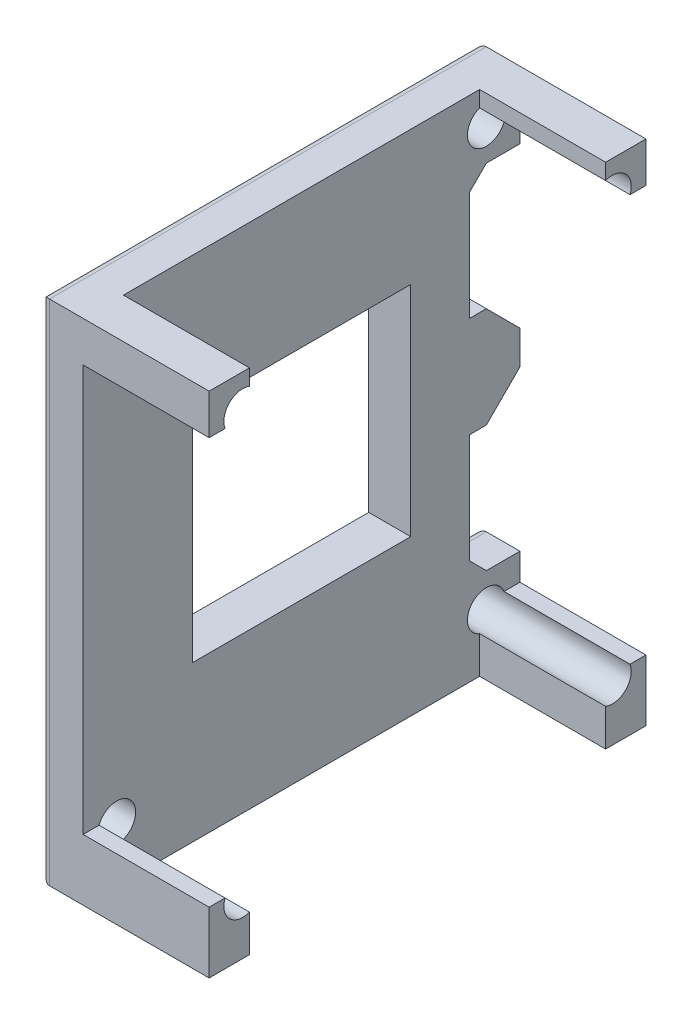
SolidWorks part; units mm, degrees
ref_plane "Front Plane" through (0, 0, 0) normal (0, 0, 1) x (1, 0, 0)
ref_plane "Top Plane" through (0, 0, 0) normal (0, 1, 0) x (1, 0, 0)
ref_plane "Right Plane" through (0, 0, 0) normal (1, 0, 0) x (0, 0, -1)
sketch "Sketch2" plane through (0, 0, 0) normal (1, 0, 0) x (0, 0, -1)
  line L1 (21, -21) -> (-21, -21) construction
  line L2 (21, -21) -> (21, 21) construction
  line L3 (21, 21) -> (-21, 21) construction
  line L4 (-21, -21) -> (-21, 21) construction
  line L5 (21, -21) -> (-21, 21) construction
  line L6 (21, 21) -> (-21, -21) construction
  line L7 (13, -13) -> (-13, -13)
  line L8 (13, -13) -> (13, 13)
  line L9 (13, 13) -> (-13, 13)
  line L10 (-13, -13) -> (-13, 13)
  line L11 (13, -13) -> (-13, 13) construction
  line L12 (13, 13) -> (-13, -13) construction
  line L13 (26, -29) -> (-26, -29)
  line L14 (26, -29) -> (26, 29)
  line L15 (26, 29) -> (-26, 29)
  line L16 (-26, -29) -> (-26, 29)
  line L17 (26, -29) -> (-26, 29) construction
  line L18 (26, 29) -> (-26, -29) construction
  point P0 (0, 0)
  point P6 (0, 0)
  point P11 (0, 0)
  dimension "D1" = 42
  dimension "D2" = 8
  dimension "D3" = 5
  dimension "D4" = 8
extrude "Boss-Extrude1" add sketch "Sketch2" along normal blind 5
sketch "Sketch3" plane through (5, 0, 0) normal (1, 0, 0) x (0, 0, -1)
  line L1 (-26, 29) -> (-21.2, 29)
  line L2 (-26, 29) -> (-26, 24.2)
  line L3 (-26, 24.2) -> (-21.2, 24.2)
  line L4 (-21.2, 29) -> (-21.2, 24.2)
  dimension "D1" = 4.8
extrude "Boss-Extrude2" add sketch "Sketch3" along normal blind 15
sketch "Sketch5" plane through (0, 0, 0) normal (-1, 0, 0) x (0, 0, 1)
  line L0 (-26, 29) -> (26, 29) construction
  line L1 (26, 29) -> (26, -29) construction
  point P0 (22, 25)
  dimension "D1" = 4
  dimension "D2" = 4
hole_wizard "M4 Clearance Hole1" positions "3DSketch1" profile "Sketch6" hole size "M4" standard "BSI" end condition through all
sketch3d "3DSketch1"
  point P0 (0, 25, 22)
sketch "Sketch6" plane through (0, 25, 22) normal (0, 1, 0) x (0, 0, 1)
  line L0 (0, 0) -> (0, 20)
  line L1 (0, 20) -> (2.25, 20)
  line L2 (2.25, 20) -> (2.25, 0)
  line L5 (2.25, 0) -> (0, 0)
  line L11 (0, -6.35) -> (0, 107.95) construction
  dimension "Thru Hole Dia." = 4.5
  dimension "Thru Hole Depth" = 20
mirror "Mirror1" about plane through (0, 0, 0) normal (0, 0, 1) of "M4 Clearance Hole1", "Boss-Extrude2"
mirror "Mirror2" about plane through (0, 0, 0) normal (0, 1, 0) of "Mirror1", "Boss-Extrude2", "M4 Clearance Hole1"
sketch "Sketch7" plane through (0, 0, 0) normal (-1, 0, 0) x (0, 0, 1)
  line L0 (-26, -29) -> (-26, 29) construction
  line L1 (-26, 21) -> (-20, 21)
  line L2 (-26, 21) -> (-26, 6)
  line L3 (-26, 6) -> (-20, 6)
  line L4 (-20, 21) -> (-20, 6)
  line L5 (-26, 29) -> (26, 29) construction
  dimension "D1" = 15
  dimension "D2" = 8
  dimension "D3" = 6
extrude "Cut-Extrude1" cut sketch "Sketch7" against normal through all
mirror "Mirror3" about plane through (0, 0, 0) normal (0, 1, 0) of "Cut-Extrude1"
sketch "Sketch8" plane through (5, 0, 0) normal (1, 0, 0) x (0, 0, -1)
  line L0 (-21, 21) -> (-21, 19)
  line L1 (21, -21) -> (-21, -21) construction
  line L2 (21, -21) -> (21, 21) construction
  line L3 (21, 21) -> (-21, 21) construction
  line L4 (-21, -21) -> (-21, 21) construction
  line L5 (21, -21) -> (-21, 21) construction
  line L6 (21, 21) -> (-21, -21) construction
  line L7 (20, -20) -> (-20, -20) construction
  line L8 (20, -20) -> (20, 20) construction
  line L9 (20, 20) -> (-20, 20) construction
  line L10 (-20, -20) -> (-20, 20) construction
  line L11 (20, -20) -> (-20, 20) construction
  line L12 (20, 20) -> (-20, -20) construction
  line L13 (-21, 19) -> (-20, 19)
  line L14 (-20, 19) -> (-20, 20)
  line L15 (-20, 20) -> (-19, 20)
  line L16 (-19, 20) -> (-19, 21)
  line L17 (-19, 21) -> (-21, 21)
  point P0 (0, 0)
  point P6 (0, 0)
  dimension "D1" = 40
  dimension "D2" = 42
  dimension "D3" = 1
extrude "Boss-Extrude3" [suppressed] add sketch "Sketch8" along normal blind 2
mirror "Mirror4" [suppressed] about plane through (0, 0, 0) normal (0, 0, 1)
mirror "Mirror5" [suppressed] about plane through (0, 0, 0) normal (0, 1, 0)
chamfer "Chamfer1" distance 2 angle 45 2 edges at (2.5, -21, -20) (2.5, 21, -20)
sketch "Sketch9" plane through (0, -29, 0) normal (0, -1, 0) x (1, 0, 0)
  line L8 (0, 26) -> (0, -26)
  line L9 (0, -26) -> (20, -26)
  line L10 (20, -26) -> (20, -21.2)
  line L11 (20, -21.2) -> (5, -21.2)
  line L12 (5, -21.2) -> (5, 21.2)
  line L13 (5, 21.2) -> (20, 21.2)
  line L14 (20, 21.2) -> (20, 26)
  line L15 (20, 26) -> (0, 26)
  line L16 (0, 26) -> (0, -26)
  line L17 (0, -26) -> (20, -26)
  line L18 (20, -26) -> (20, -21.2)
  line L19 (20, -21.2) -> (5, -21.2)
  line L20 (5, -21.2) -> (5, 21.2)
  line L21 (5, 21.2) -> (20, 21.2)
  line L22 (20, 21.2) -> (20, 26)
  line L23 (20, 26) -> (0, 26)
  dimension "D1" = 0
extrude "Boss-Extrude4" add sketch "Sketch9" along normal blind 2.5
chamfer "Chamfer2" distance 4 angle 45 2 edges at (2.5, 6, -26) (2.5, -6, -26)
fillet "Fillet1" radius 1 15 edges at (0, -1.25, 26) (0, -31.5, 0) (0, -26.25, -26) (0, -21, -24) (0, -20, -21) (0, -12.5, -20) (0, -6, -21) (0, -4, -24) (0, 0, -26) (0, 4, -24) (0, 6, -21) (0, 12.5, -20) (0, 20, -21) (0, 21, -24) (0, 29, 0)
equation "\"D2@Sketch5\"=\"D1@Sketch5\""
